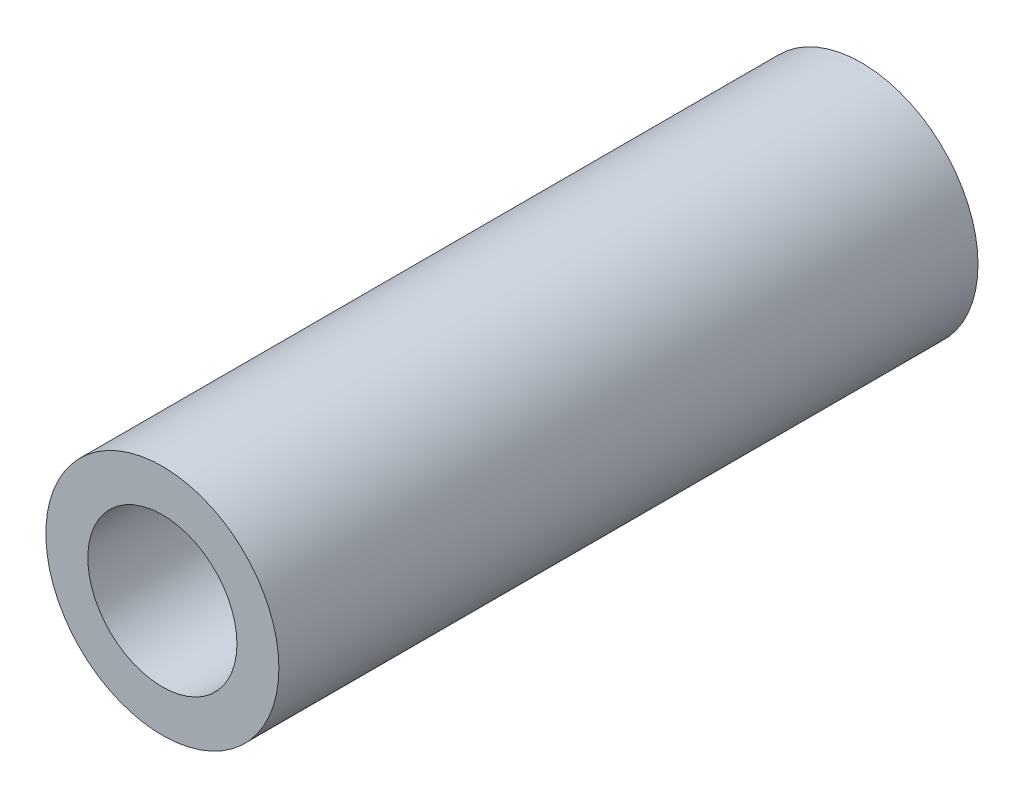
SolidWorks part; units mm, degrees
ref_plane "前视基准面" through (0, 0, 0) normal (0, 0, 1) x (1, 0, 0)
ref_plane "上视基准面" through (0, 0, 0) normal (0, 1, 0) x (1, 0, 0)
ref_plane "右视基准面" through (0, 0, 0) normal (1, 0, 0) x (0, 0, -1)
sketch "草图1" plane through (0, 0, 0) normal (0, 0, 1) x (1, 0, 0)
  circle A0 centre (0, 0) radius 3.2
  circle A1 centre (0, 0) radius 5
  dimension "D1" = 6.4
  dimension "D2" = 10
extrude "凸台-拉伸1" add sketch "草图1" along normal blind 30
